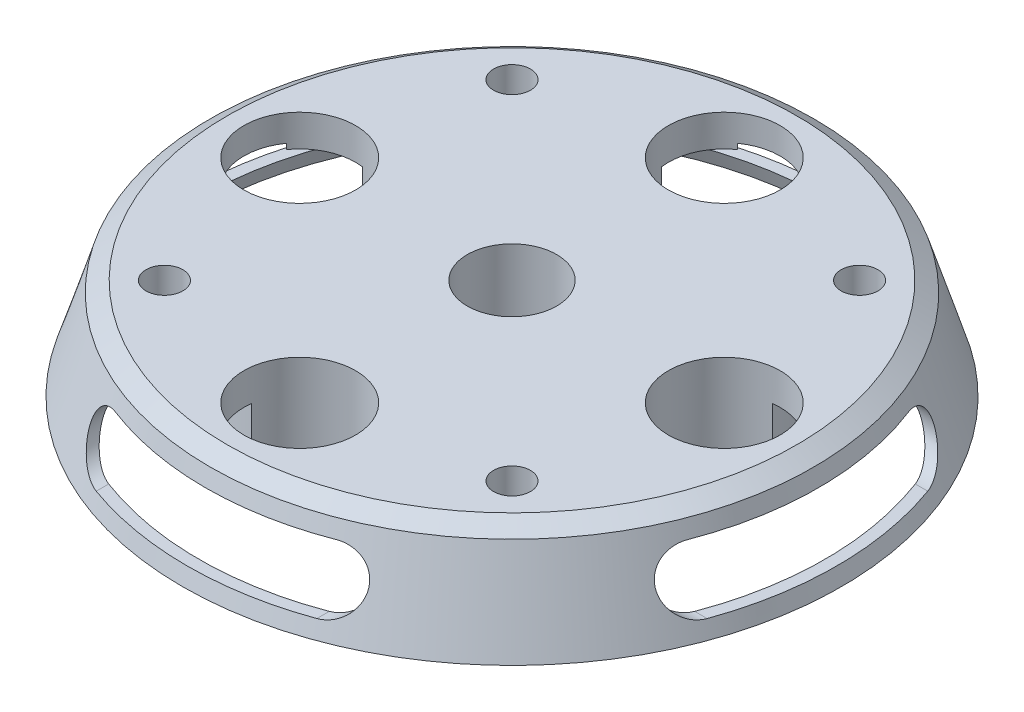
SolidWorks part; units mm, degrees
material "6061 Alloy"
ref_plane "Front Plane" through (0, 0, 0) normal (0, 0, 1) x (1, 0, 0)
ref_plane "Top Plane" through (0, 0, 0) normal (0, 1, 0) x (1, 0, 0)
ref_plane "Right Plane" through (0, 0, 0) normal (1, 0, 0) x (0, 0, -1)
sketch "Sketch1" plane through (0, 0, 0) normal (1, 0, 0) x (0, 0, -1)
  line L0 (0, 9) -> (0, 6.15)
  line L1 (29.5, 0) -> (27.0118, 8.023)
  line L2 (27.0118, 8.023) -> (25.5, 9)
  line L3 (25.5, 9) -> (0, 9)
  line L4 (28.453, 0) -> (29.5, 0)
  line L5 (0, 6.15) -> (26.5457, 6.15)
  line L6 (26.5457, 6.15) -> (28.453, 0)
  dimension "D1" = 9
  dimension "D2" = 29.5
  dimension "D3" = 8.4
  dimension "D4" = 1.8
  dimension "D5" = 25.5
  dimension "D6" = 2.85
  dimension "D7" = 1
revolve "Revolve1" add sketch "Sketch1" angle 360 about L0
sketch "Sketch2" plane through (0, 6.15, 0) normal (0, -1, 0) x (1, 0, 0)
  circle A0 centre (0, 0) radius 19
  dimension "D1" = 38
extrude "Boss-Extrude1" add sketch "Sketch2" along normal blind 5
sketch "Sketch3" plane through (0, 9, 0) normal (0, 1, 0) x (1, 0, 0)
  circle A0 centre (0, 19) radius 5
  circle A1 centre (19, 0) radius 5
  circle A2 centre (0, -19) radius 5
  circle A3 centre (-19, 0) radius 5
  point P12 (0, 0)
  dimension "D1" = 10
  dimension "D2" = 19
  dimension "D3" = 4
extrude "Cut-Extrude1" cut sketch "Sketch3" against normal through all
sketch "Sketch4" plane through (0, 9, 0) normal (0, 1, 0) x (1, 0, 0)
  circle A0 centre (0, 0) radius 4
  dimension "D1" = 8
extrude "Cut-Extrude2" cut sketch "Sketch4" against normal through all
sketch "Sketch5" plane through (0, 9, 0) normal (0, 1, 0) x (1, 0, 0)
  line L0 (-19, 0) -> (0, 19) construction
  line L1 (0, 0) -> (-16.2201, 16.2201) construction
  point P7 (-15.5563, 15.5563)
  point P11 (15.5563, 15.5563)
  point P12 (15.5563, -15.5563)
  point P13 (-15.5563, -15.5563)
  point P14 (0, 0)
  dimension "D1" = 22
  dimension "D2" = 4
hole_wizard "M4x0.7 Tapped Hole1" positions "Sketch7" profile "Sketch6" tap size "M4x0.7" standard "ANSI Metric" end condition through all
sketch "Sketch7" plane through (0, 9, 0) normal (0, 1, 0) x (1, 0, 0)
  point P0 (-15.5563, 15.5563)
  point P3 (15.5563, 15.5563)
  point P6 (15.5563, -15.5563)
  point P9 (-15.5563, -15.5563)
sketch "Sketch6" plane through (-15.5563, 9, -15.5563) normal (1, 0, 0) x (0, 0, 1)
  line L0 (0, 0) -> (0, 9)
  line L1 (0, 9) -> (1.65, 9)
  line L2 (1.65, 9) -> (1.65, 0)
  line L5 (1.65, 0) -> (0, 0)
  line L11 (0, -6.35) -> (0, 107.95) construction
  dimension "Thru Tap Drill Dia." = 3.3
  dimension "Thru Tap Drill Depth" = 9
cosmetic thread "Hole Thread1" parameters "D2"=4
cosmetic thread "Hole Thread2" parameters "D2"=4
cosmetic thread "Hole Thread3" parameters "D2"=4
cosmetic thread "Hole Thread4" parameters "D2"=4
sketch "Sketch8" plane through (0, 0, 0) normal (0, -1, 0) x (-1, 0, 0)
  line L0 (0, 29.5) -> (0, 0) construction
  circle A0 centre (0, 0) radius 29.5 construction
  point P6 (0, 29.5)
ref_plane "Plane1" through (0, 0, -29.5) normal (0, 0, 1) x (1, 0, 0)
sketch "Sketch9" plane through (0, 0, -29.5) normal (0, 0, 1) x (1, 0, 0)
  line L0 (0, 0) -> (0, 8.023) construction
  line L1 (27.0118, 8.023) -> (-27.0118, 8.023) construction
  line L2 (0, 4.0115) -> (12.5286, 4.0115) construction
  line L3 (-9.875, 6.6365) -> (9.875, 6.6365)
  line L4 (-9.875, 1.3865) -> (9.875, 1.3865)
  line L5 (12.5, 4.0115) -> (-12.5, 4.0115) construction
  arc A0 (9.875, 6.6365) -> (9.875, 1.3865) centre (9.875, 4.0115) cw
  arc A1 (-9.875, 6.6365) -> (-9.875, 1.3865) centre (-9.875, 4.0115) ccw
  point P13 (0, 1.3865)
  point P14 (0, 6.6365)
  dimension "D1" = 5.25
  dimension "D2" = 25
extrude "Cut-Extrude3" cut sketch "Sketch9" along normal blind 6.43
pattern_circular "CirPattern1" count 4 over 360 about axis through (0, 0, 0) along (0, 1, 0) of "Cut-Extrude3"
sketch "Sketch10" plane through (0, 9, 0) normal (0, 1, 0) x (1, 0, 0)
  point P0 (-15.5563, 15.5563)
